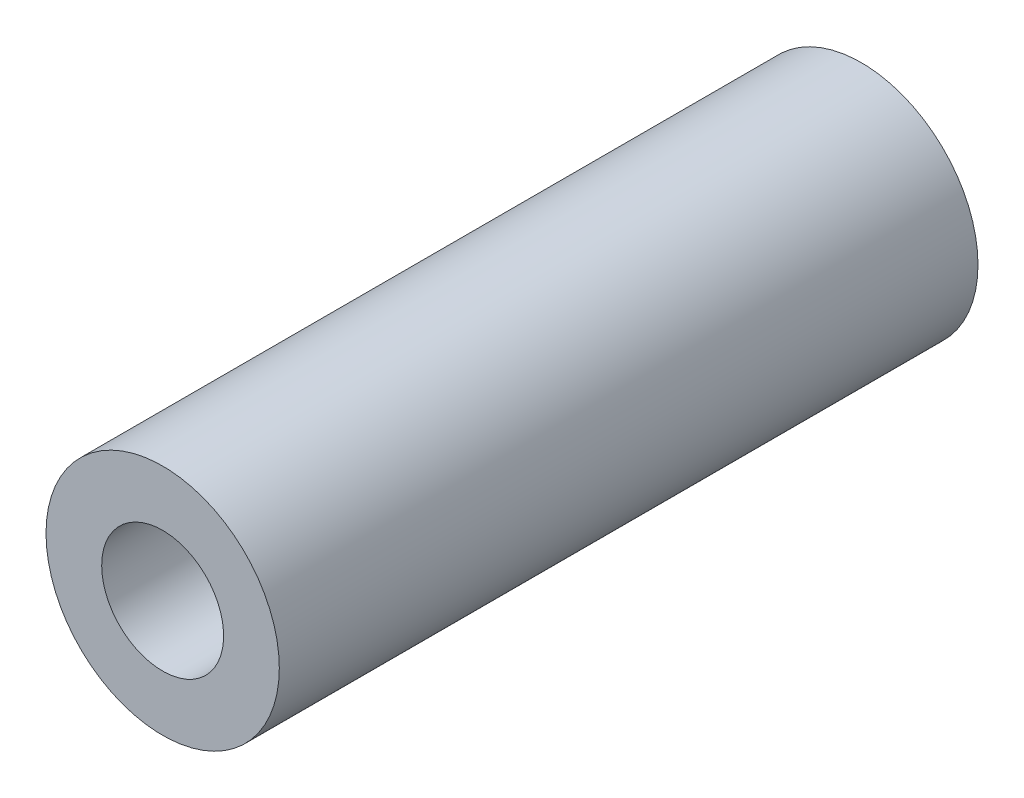
SolidWorks part; units mm, degrees
material "6061-T6 (SS)"
ref_plane "Front Plane" through (0, 0, 0) normal (0, 0, 1) x (1, 0, 0)
ref_plane "Top Plane" through (0, 0, 0) normal (0, 1, 0) x (1, 0, 0)
ref_plane "Right Plane" through (0, 0, 0) normal (1, 0, 0) x (0, 0, -1)
sketch "Sketch1" plane through (0, 0, 0) normal (0, 0, 1) x (1, 0, 0)
  circle A0 centre (0, 0) radius 2.4892
  circle A1 centre (0, 0) radius 4.7625
  dimension "D1" = 4.9784
  dimension "D2" = 9.525
extrude "Boss-Extrude1" add sketch "Sketch1" along normal mid plane 28.5242
